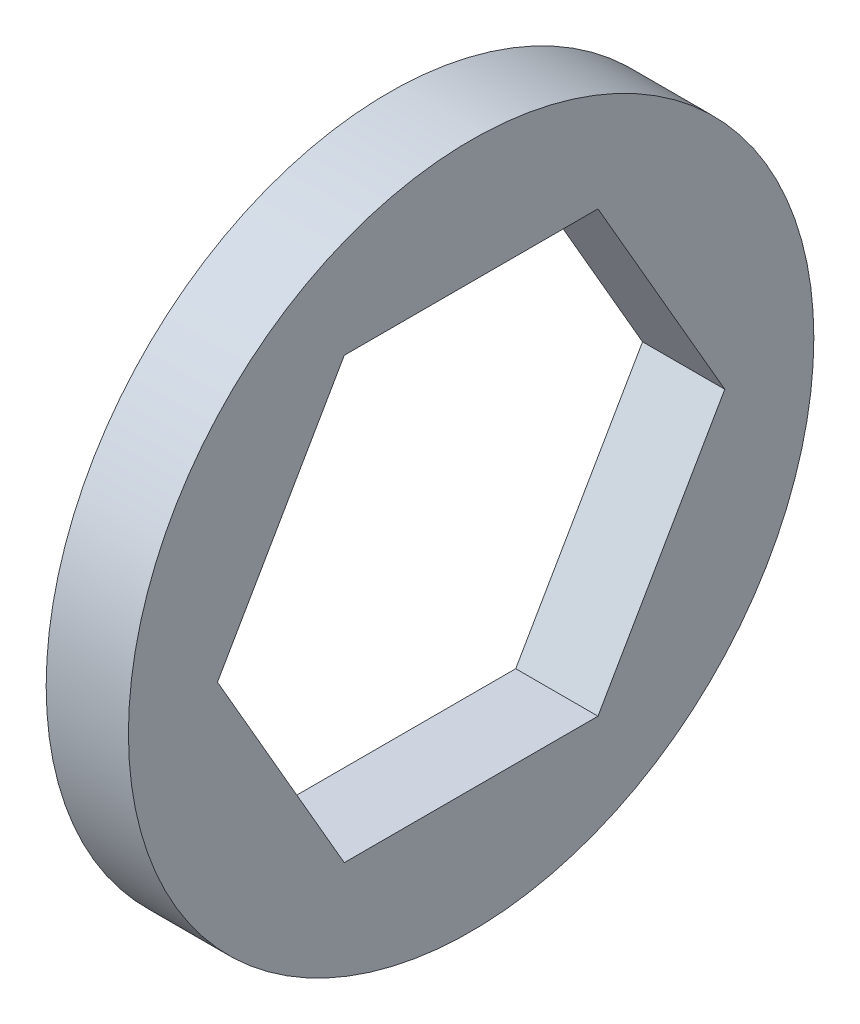
SolidWorks part; units mm, degrees
ref_plane "Front Plane" through (0, 0, 0) normal (0, 0, 1) x (1, 0, 0)
ref_plane "Top Plane" through (0, 0, 0) normal (0, 1, 0) x (1, 0, 0)
ref_plane "Right Plane" through (0, 0, 0) normal (1, 0, 0) x (0, 0, -1)
sketch "Sketch1" plane through (0, 0, 0) normal (1, 0, 0) x (0, 0, -1)
  line L1 (18.5041, 0) -> (9.252, 16.025)
  line L2 (9.252, 16.025) -> (-9.252, 16.025)
  line L3 (-9.252, 16.025) -> (-18.5041, 0)
  line L4 (-18.5041, 0) -> (-9.252, -16.025)
  line L5 (-9.252, -16.025) -> (9.252, -16.025)
  line L6 (9.252, -16.025) -> (18.5041, 0)
  circle A0 centre (0, 0) radius 25
  circle A1 centre (0, 0) radius 16.025 construction
  point P3 (0, 0)
  dimension "D1" = 50
  dimension "D2" = 32.05
extrude "Boss-Extrude1" add sketch "Sketch1" along normal blind 6
